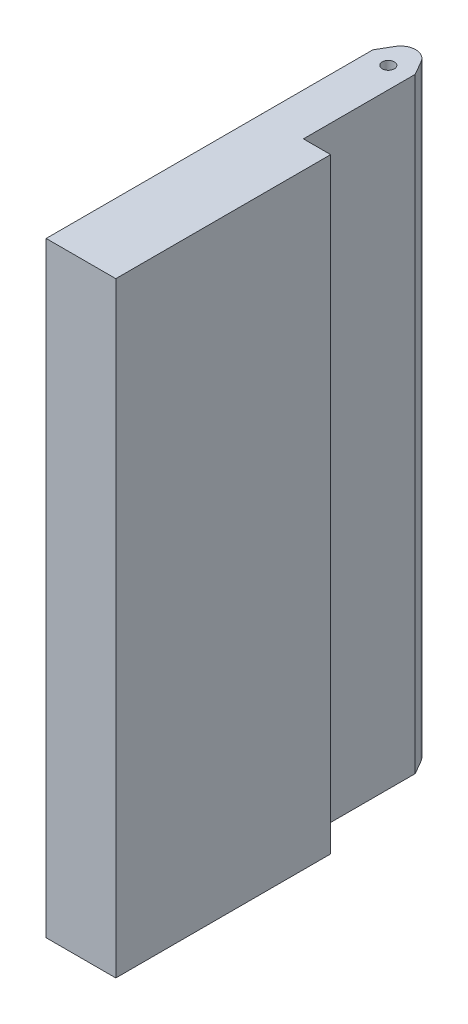
SolidWorks part; units mm, degrees
ref_plane "Front Plane" through (0, 0, 0) normal (0, 0, 1) x (1, 0, 0)
ref_plane "Top Plane" through (0, 0, 0) normal (0, 1, 0) x (1, 0, 0)
ref_plane "Right Plane" through (0, 0, 0) normal (1, 0, 0) x (0, 0, -1)
sketch "Sketch1" plane through (0, 0, 0) normal (0, 1, 0) x (1, 0, 0)
  line L1 (-11, 60) -> (11, 60)
  line L2 (-11, 60) -> (-11, -60)
  line L3 (-11, -60) -> (11, -60)
  line L4 (11, 60) -> (11, -60)
  line L5 (-11, 60) -> (11, -60) construction
  line L6 (-11, -60) -> (11, 60) construction
  point P0 (0, 0)
  dimension "D1" = 120
  dimension "D2" = 22
extrude "Boss-Extrude1" add sketch "Sketch1" along normal blind 200
sketch "Sketch2" plane through (0, 200, 0) normal (0, 1, 0) x (1, 0, 0)
  line L0 (0, 60) -> (-11, 40.9474)
  line L1 (11, 60) -> (-11, 60) construction
  line L2 (-11, 60) -> (-11, -60) construction
  line L3 (-11, 40.9474) -> (-11, -60)
  line L4 (-11, -60) -> (11, -60)
  line L5 (11, -60) -> (11, 40.9474)
  line L6 (11, -60) -> (11, 60) construction
  line L7 (11, 40.9474) -> (0, 60)
  dimension "D1" = 60
  dimension "D2" = 0
extrude "Cut-Extrude1" cut sketch "Sketch2" against normal through all flip side to cut
fillet "Fillet1" radius 5 1 edges at (0, 100, -60)
sketch "Sketch3" plane through (0, 200, 0) normal (0, 1, 0) x (1, 0, 0)
  line L0 (-11, 36.9474) -> (-7, 36.9474)
  line L1 (-11, 40.9474) -> (-11, -60) construction
  line L2 (-7, 36.9474) -> (-7, 47.8756)
  line L3 (-4.3301, 52.5) -> (-11, 40.9474) construction
  line L4 (-7, 47.8756) -> (-11, 40.9474)
  line L5 (-11, 40.9474) -> (-11, 36.9474)
  line L6 (7, 47.8756) -> (11, 40.9474)
  line L7 (11, 40.9474) -> (4.3301, 52.5) construction
  line L8 (11, 40.9474) -> (11, 36.9474)
  line L9 (11, -60) -> (11, 40.9474) construction
  line L10 (11, 36.9474) -> (7, 36.9474)
  line L11 (7, 36.9474) -> (7, 47.8756)
  dimension "D1" = 4
  dimension "D2" = 4
  dimension "D3" = 4
  dimension "D4" = 4
extrude "Cut-Extrude2" cut sketch "Sketch3" against normal through all
sketch "Sketch4" plane through (11, 0, 0) normal (1, 0, 0) x (0, 0, -1)
  line L1 (-60, 200) -> (36.9474, 200)
  line L2 (-60, 200) -> (-60, 0)
  line L3 (-60, 0) -> (36.9474, 0)
  line L4 (36.9474, 200) -> (36.9474, 0)
extrude "Boss-Extrude2" add sketch "Sketch4" along normal blind 5
sketch "Sketch5" plane through (0, 200, 0) normal (0, 1, 0) x (1, 0, 0)
  line L1 (-7, 36.9474) -> (-11, 36.9474)
  line L2 (-7, 36.9474) -> (-7, -60)
  line L3 (-7, -60) -> (-11, -60)
  line L4 (-11, 36.9474) -> (-11, -60)
extrude "Cut-Extrude3" cut sketch "Sketch5" against normal through all
sketch "Sketch6" plane through (0, 200, 0) normal (0, 1, 0) x (1, 0, 0)
  circle A0 centre (0, 46) radius 2
  arc A1 (4.3301, 52.5) -> (-4.3301, 52.5) centre (0, 50) ccw construction
  dimension "D1" = 4
extrude "Cut-Extrude4" cut sketch "Sketch6" against normal through all
sketch "Sketch8" plane through (0, 200, 0) normal (0, 1, 0) x (1, 0, 0)
  line L0 (16, 36.9474) -> (16, -60) construction
  line L1 (7, 36.9474) -> (16, 36.9474)
  line L2 (7, 36.9474) -> (7, 10.9474)
  line L3 (7, 10.9474) -> (16, 10.9474)
  line L4 (16, 36.9474) -> (16, 10.9474)
  dimension "D1" = 26
extrude "Cut-Extrude5" cut sketch "Sketch8" against normal through all
